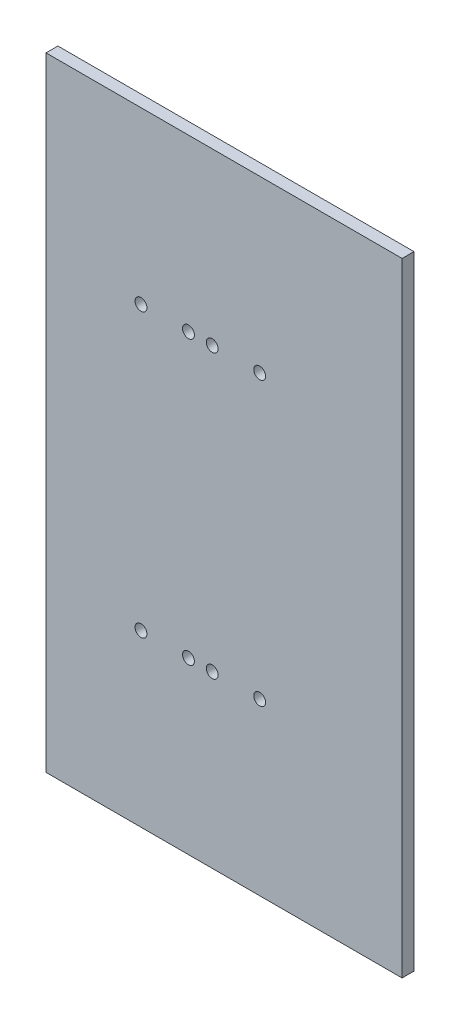
SolidWorks part; units mm, degrees
material "自訂玻璃纖維"
ref_plane "前基準面" through (0, 0, 0) normal (0, 0, 1) x (1, 0, 0)
ref_plane "上基準面" through (0, 0, 0) normal (0, 1, 0) x (1, 0, 0)
ref_plane "右基準面" through (0, 0, 0) normal (1, 0, 0) x (0, 0, -1)
sketch "草圖1" plane through (0, 0, 0) normal (0, 0, 1) x (1, 0, 0)
  line L1 (-36.9718, 43.0126) -> (23.0282, 43.0126)
  line L2 (-36.9718, 43.0126) -> (-36.9718, -61.9874)
  line L3 (-36.9718, -61.9874) -> (23.0282, -61.9874)
  line L4 (23.0282, 43.0126) -> (23.0282, -61.9874)
  circle A6 centre (-12.9718, -33.2874) radius 1
  circle A7 centre (-8.9718, -33.2874) radius 1
  circle A8 centre (-12.9718, 14.3126) radius 1
  circle A9 centre (-20.9718, 14.3126) radius 1
  circle A10 centre (-0.9718, 14.3126) radius 1
  circle A11 centre (-8.9718, 14.3126) radius 1
  circle A12 centre (-20.9718, -33.2874) radius 1
  circle A13 centre (-0.9718, -33.2874) radius 1
  point P0 (-36.9718, 43.0126)
  point P1 (23.0282, -61.9874)
  point P8 (23.0282, -61.9874)
  point P11 (23.0282, 43.0126)
  point P14 (-36.9718, 43.0126)
  dimension "D5" = 0
  dimension "D11" = 0
  dimension "D1" = 60
  dimension "D2" = 105
  dimension "D12" = 0
extrude "填料-伸長1" add sketch "草圖1" along normal blind 2
